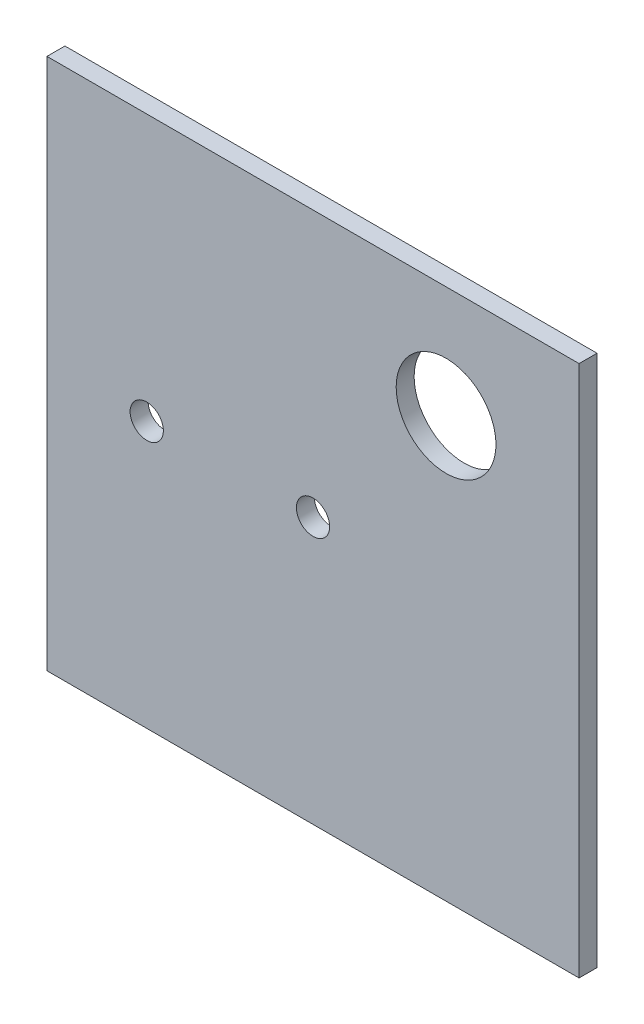
SolidWorks part; units mm, degrees
material "Acrílico (Impacto medio-alto)"
ref_plane "Alzado" through (0, 0, 0) normal (0, 0, 1) x (1, 0, 0)
ref_plane "Planta" through (0, 0, 0) normal (0, 1, 0) x (1, 0, 0)
ref_plane "Vista lateral" through (0, 0, 0) normal (1, 0, 0) x (0, 0, -1)
sketch "Croquis1" plane through (0, 0, 0) normal (0, 0, 1) x (1, 0, 0)
  line L1 (-82.7, 40) -> (-2.7, 40)
  line L2 (-82.7, 40) -> (-82.7, -40)
  line L3 (-82.7, -40) -> (-2.7, -40)
  line L4 (-2.7, 40) -> (-2.7, -40)
extrude "Saliente-Extruir2" add sketch "Croquis1" against normal blind 2.7
sketch "Croquis2" plane through (0, 0, -2.7) normal (0, 0, -1) x (-1, 0, 0)
  line L0 (42.7, 40) -> (42.7, -40) construction
  line L1 (2.7, 40) -> (82.7, 40) construction
  line L2 (82.7, -40) -> (2.7, -40) construction
  line L3 (42.7, 0) -> (82.7, 0) construction
  line L4 (82.7, 40) -> (82.7, -40) construction
  circle A0 centre (67.7, 0) radius 2.5
  circle A1 centre (42.7, 0) radius 2.5
  dimension "D1" = 5
  dimension "D2" = 15
  dimension "D3" = 40
extrude "Cortar-Extruir1" cut sketch "Croquis2" against normal blind 2.7
sketch "Croquis4" plane through (0, 0, -2.7) normal (0, 0, -1) x (-1, 0, 0)
  circle A0 centre (22.7, 23.2) radius 7.5
extrude "Cortar-Extruir2" cut sketch "Croquis4" against normal blind 2.7
